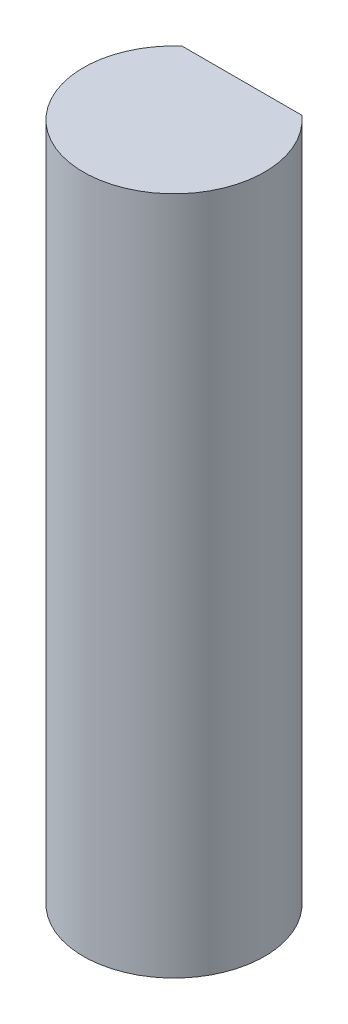
SolidWorks part; units mm, degrees
ref_plane "Front Plane" through (0, 0, 0) normal (0, 0, 1) x (1, 0, 0)
ref_plane "Top Plane" through (0, 0, 0) normal (0, 1, 0) x (1, 0, 0)
ref_plane "Right Plane" through (0, 0, 0) normal (1, 0, 0) x (0, 0, -1)
sketch "Sketch1" plane through (0, 0, 0) normal (0, 1, 0) x (1, 0, 0)
  line L0 (1.3229, 1.5) -> (-1.3229, 1.5)
  arc A0 (-1.3229, 1.5) -> (1.3229, 1.5) centre (0, 0) ccw
  dimension "D1" = 4
  dimension "D2" = 1.5
extrude "Boss-Extrude1" add sketch "Sketch1" along normal blind 15
